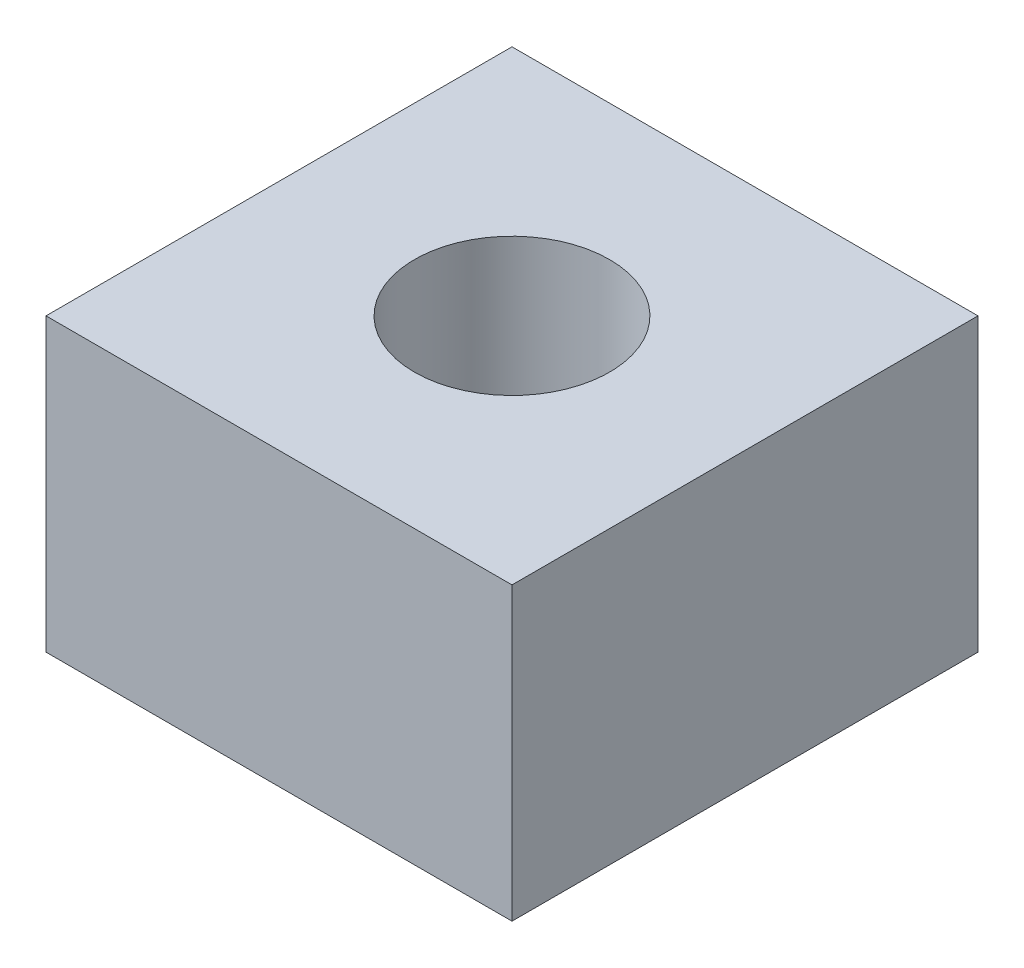
SolidWorks part; units mm, degrees
ref_plane "Front Plane" through (0, 0, 0) normal (0, 0, 1) x (1, 0, 0)
ref_plane "Top Plane" through (0, 0, 0) normal (0, 1, 0) x (1, 0, 0)
ref_plane "Right Plane" through (0, 0, 0) normal (1, 0, 0) x (0, 0, -1)
sketch "Sketch2" plane through (0, 0, 0) normal (0, 1, 0) x (1, 0, 0)
  line L0 (4.4708, 9.3994) -> (4.4708, 13.3994)
  line L1 (12.4708, 13.3994) -> (12.4708, 9.3994)
  line L2 (12.4708, 9.3994) -> (4.4708, 9.3994)
  line L3 (4.4708, 13.3994) -> (4.4708, 17.3994)
  line L4 (4.4708, 17.3994) -> (12.4708, 17.3994)
  line L5 (12.4708, 17.3994) -> (12.4708, 13.3994)
  circle A1 centre (8.4708, 13.3994) radius 1.675
  dimension "D2" = 3.35
  dimension "D1" = 4
  dimension "D3" = 8
  dimension "D4" = 4
extrude "Boss-Extrude1" add sketch "Sketch2" along normal blind 5
